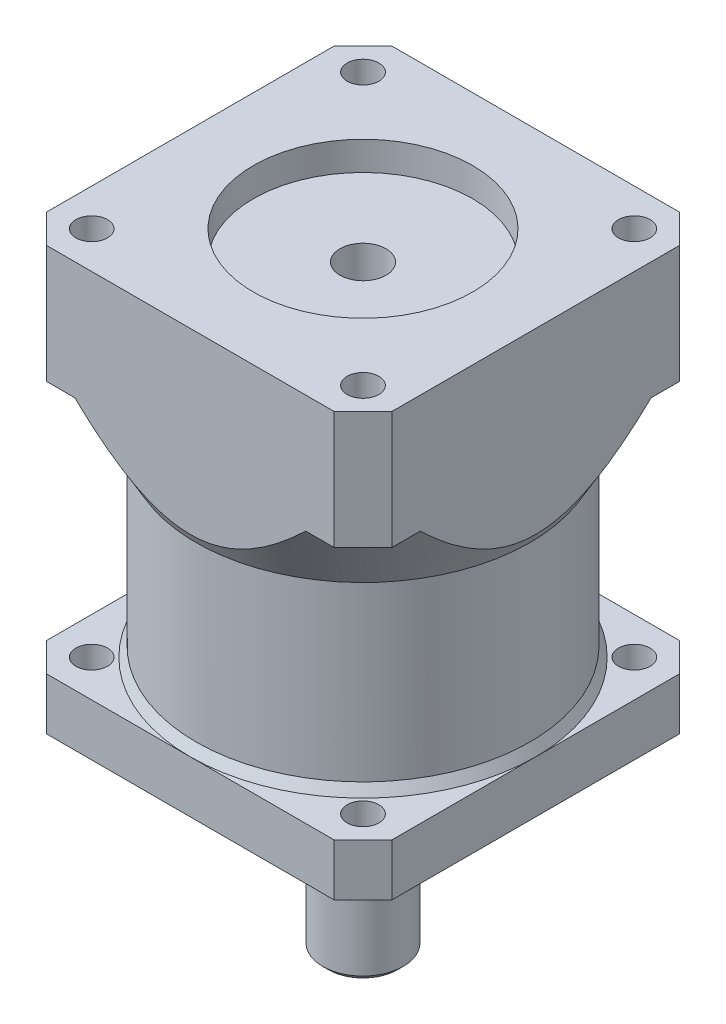
SolidWorks part; units mm, degrees
material "AISI 304"
ref_plane "Płaszczyzna przednia" through (0, 0, 0) normal (0, 0, 1) x (1, 0, 0)
ref_plane "Płaszczyzna górna" through (0, 0, 0) normal (0, 1, 0) x (1, 0, 0)
ref_plane "Płaszczyzna prawa" through (0, 0, 0) normal (1, 0, 0) x (0, 0, -1)
sketch "Szkic1" plane through (0, 0, 0) normal (0, 1, 0) x (1, 0, 0)
  line L1 (-30, 30) -> (30, 30)
  line L2 (-30, 30) -> (-30, -30)
  line L3 (-30, -30) -> (30, -30)
  line L4 (30, 30) -> (30, -30)
  line L5 (-30, 30) -> (30, -30) construction
  line L6 (-30, -30) -> (30, 30) construction
  point P0 (0, 0)
  dimension "D1" = 60
extrude "Dodanie-wyciągnięcie1" add sketch "Szkic1" along normal mid plane 73.5
sketch "Szkic2" plane through (0, 0, 0) normal (0, 0, 1) x (1, 0, 0)
  line L0 (0, 0) -> (0, 50000) construction
  line L1 (29, 4.0179) -> (30, 5.75)
  line L2 (30, 36.75) -> (30, -36.75) construction
  line L4 (30, -27.7141) -> (29, -25.9821)
  line L5 (29, -25.9821) -> (29, 4.0179)
  line L6 (-30, 36.75) -> (30, 36.75) construction
  line L10 (30, 5.75) -> (36.0803, 16.2814)
  line L11 (36.0803, 16.2814) -> (59, 16.2814)
  line L12 (59, 16.2814) -> (59, -27.7141)
  line L14 (30, -27.7141) -> (59, -27.7141)
  dimension "D1" = 58
  dimension "D2" = 30
  dimension "D3" = 30
  dimension "D4" = 31
  dimension "D5" = 30
  dimension "D6" = 30
revolve "Wycięcie-obrót1" cut sketch "Szkic2" angle 360 about L0
chamfer "Sfazowanie1" distance 5 angle 45 8 edges at (30, -32.2321, -30) (30, 26.5157, -30) (-30, 26.5157, -30) (-30, -32.2321, -30) (-30, 26.5157, 30) (30, 26.5157, 30) (30, -32.2321, 30) (-30, -32.2321, 30)
sketch "Szkic4" plane through (0, 0, 0) normal (0, 0, 1) x (1, 0, 0)
  line L0 (0, 0) -> (0, 50000) construction
  line L1 (0, 36.75) -> (19.05, 36.75)
  line L2 (-25, 36.75) -> (25, 36.75) construction
  line L3 (19.05, 36.75) -> (19.05, 31.75)
  line L4 (19.05, 31.75) -> (4, 31.75)
  line L5 (4, 31.75) -> (4, 16.75)
  line L6 (4, 16.75) -> (0, 16.75)
  line L7 (0, 16.75) -> (0, 36.75)
  dimension "D1" = 8
  dimension "D2" = 5
  dimension "D3" = 38.1
  dimension "D4" = 20
revolve "Wycięcie-obrót3" cut sketch "Szkic4" angle 360 about L0
sketch "Szkic5" plane through (0, 0, 0) normal (1, 0, 0) x (0, 0, -1)
  line L0 (0, 0) -> (0, -50000) construction
  line L1 (0, -36.75) -> (20, -36.75)
  line L2 (-25, -36.75) -> (25, -36.75) construction
  line L3 (20, -36.75) -> (20, -39.25)
  line L4 (20, -39.25) -> (9, -39.25)
  line L5 (9, -39.25) -> (9, -40.75)
  line L6 (9, -40.75) -> (7, -40.75)
  line L7 (7, -40.75) -> (7, -71.75)
  line L8 (7, -71.75) -> (0, -71.75)
  line L9 (0, -71.75) -> (0, -36.75)
  dimension "D1" = 2.5
  dimension "D2" = 35
  dimension "D3" = 18
  dimension "D4" = 40
  dimension "D5" = 14
  dimension "D6" = 31
revolve "Obrót1" add sketch "Szkic5" angle 360 about L0
chamfer "Sfazowanie2" distance 1 angle 45 1 edges at (0, -71.75, 7)
hole_wizard "Otwór pod śrubę M51" positions "Szkic6" profile "Szkic7" hole size "M5" standard "ISO"
sketch "Szkic6" plane through (0, -36.75, 0) normal (0, -1, 0) x (-1, 0, 0)
  line L0 (0, 0) -> (0, 50000) construction
  line L1 (0, 0) -> (50000, 0) construction
  line L2 (-23.57, -23.57) -> (-23.57, 23.57) construction
  line L3 (-23.57, 23.57) -> (23.57, 23.57) construction
  point P0 (-23.57, 23.57)
  point P10 (23.57, 23.57)
  point P12 (23.57, -23.57)
  point P13 (-23.57, -23.57)
  dimension "D1" = 47.14
sketch "Szkic7" plane through (23.57, -36.75, -23.57) normal (1, 0, 0) x (0, 0, -1)
  line L0 (0, 0) -> (0, 12.6524)
  line L1 (0, 12.6524) -> (2.75, 11)
  line L2 (2.75, 11) -> (2.75, 0)
  line L5 (2.75, 0) -> (0, 0)
  line L10 (0, 12.6524) -> (-2.75, 11) construction
  line L11 (0, -6.35) -> (0, 107.95) construction
  dimension "Średnica otworu" = 5.5
  dimension "Głębokość otworu" = 11
  dimension "Kąt wiertła" = 118
mirror "Lustro1" about plane through (0, 0, 0) normal (0, 1, 0) of "Otwór pod śrubę M51"
